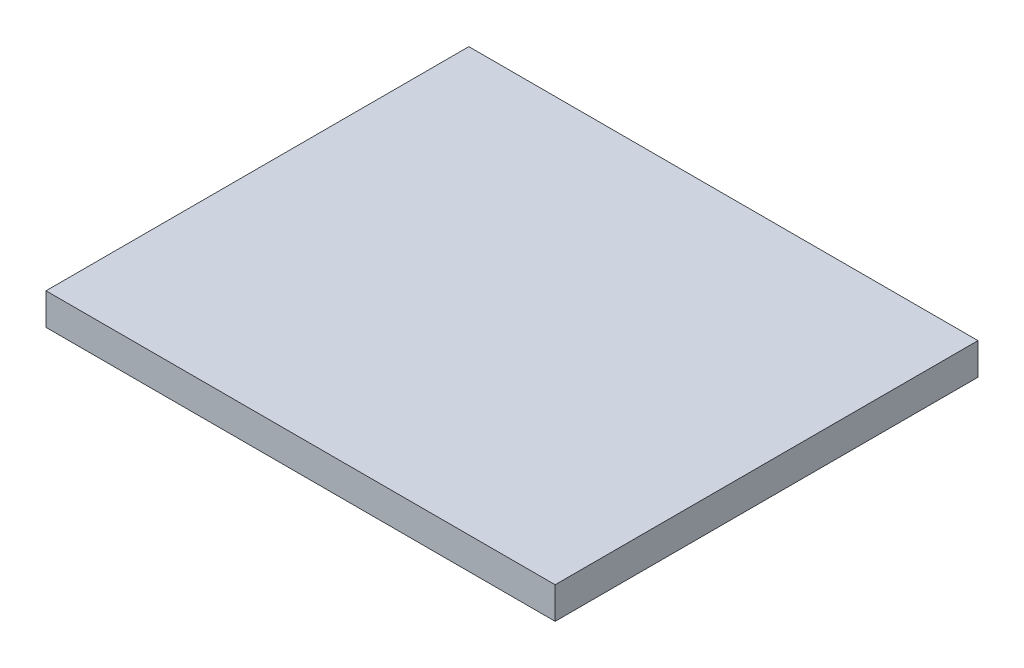
SolidWorks part; units mm, degrees
ref_plane "Front Plane" through (0, 0, 0) normal (0, 0, 1) x (1, 0, 0)
ref_plane "Top Plane" through (0, 0, 0) normal (0, 1, 0) x (1, 0, 0)
ref_plane "Right Plane" through (0, 0, 0) normal (1, 0, 0) x (0, 0, -1)
sketch "Sketch1" plane through (0, 0, 0) normal (0, 1, 0) x (1, 0, 0)
  line L1 (0, 0) -> (16.05, 0)
  line L2 (0, 0) -> (0, 13.33)
  line L3 (0, 13.33) -> (16.05, 13.33)
  line L4 (16.05, 0) -> (16.05, 13.33)
  dimension "D1" = 16.05
  dimension "D2" = 13.33
extrude "Boss-Extrude1" add sketch "Sketch1" along normal blind 1
